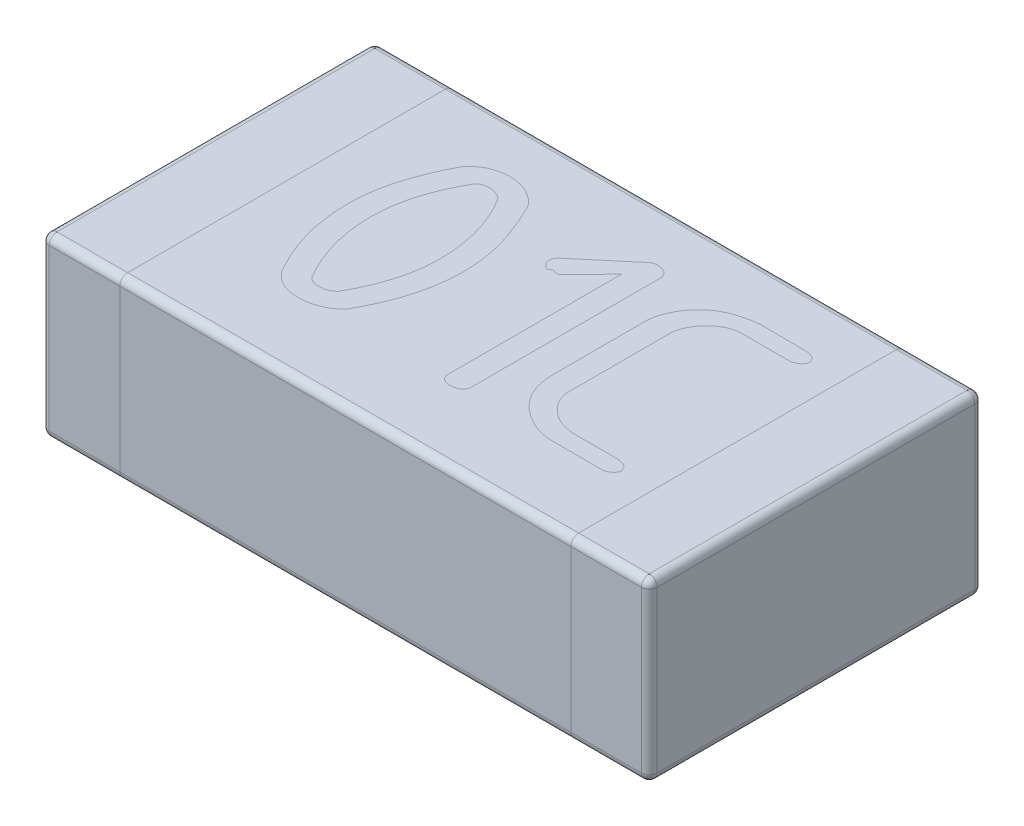
SolidWorks part; units mm, degrees
ref_plane "Front Plane" through (0, 0, 0) normal (0, 0, 1) x (1, 0, 0)
ref_plane "Top Plane" through (0, 0, 0) normal (0, 1, 0) x (1, 0, 0)
ref_plane "Right Plane" through (0, 0, 0) normal (1, 0, 0) x (0, 0, -1)
sketch "Sketch1" plane through (0, 0, 0) normal (0, 1, 0) x (1, 0, 0)
  line L1 (-0.755, -0.425) -> (0.755, -0.425)
  line L2 (-0.775, -0.405) -> (-0.775, 0.405)
  line L3 (-0.755, 0.425) -> (0.755, 0.425)
  line L4 (0.775, -0.405) -> (0.775, 0.405)
  line L5 (-0.775, -0.425) -> (0.775, 0.425) construction
  line L6 (-0.775, 0.425) -> (0.775, -0.425) construction
  arc A4 (-0.775, -0.405) -> (-0.755, -0.425) centre (-0.755, -0.405) ccw
  arc A5 (0.755, -0.425) -> (0.775, -0.405) centre (0.755, -0.405) ccw
  arc A6 (0.775, 0.405) -> (0.755, 0.425) centre (0.755, 0.405) ccw
  arc A7 (-0.755, 0.425) -> (-0.775, 0.405) centre (-0.755, 0.405) ccw
  point P0 (0, 0)
  dimension "D4" = 0.02
  dimension "D1" = 1.55
  dimension "D2" = 0.85
extrude "Boss-Extrude1" add sketch "Sketch1" along normal mid plane 0.45
sketch "Sketch3" plane through (0, 0.225, 0) normal (0, 1, 0) x (1, 0, 0)
  line L0 (-0.575, 0) -> (0.575, 0) construction
  line L1 (-0.575, -0.5133) -> (-0.575, 0.5133)
  line L2 (0.575, -0.5133) -> (0.575, 0.5133)
  line L3 (0, -0.25) -> (0, 0.25) construction
  line L6 (-0.575, -0.25) -> (0.575, -0.25) construction
  text T0 "<b>01C</b>" font "SWIsop1" height 0.53
  point P4 (0, 0)
  point P8 (-0.575, 0)
  point P11 (0.575, 0)
  point P14 (0, 0)
  point P17 (0, -0.25)
  dimension "D1" = 1.15
  dimension "D2" = 0.5
sketch "Sketch4" plane through (0, 0, 0.425) normal (0, 0, 1) x (1, 0, 0)
  line L0 (-0.575, 0.225) -> (-0.575, -0.5946)
  line L1 (0.575, 0.225) -> (0.575, -0.5946)
sketch "Sketch5" plane through (0, 0, -0.425) normal (0, 0, -1) x (-1, 0, 0)
  line L0 (-0.575, 0.225) -> (-0.575, -0.5946) construction
  line L1 (-0.575, 0.225) -> (-0.575, -0.5946)
  line L2 (0.575, 0.225) -> (0.575, -0.5946) construction
  line L3 (0.575, 0.225) -> (0.575, -0.5946)
sketch "Sketch6" plane through (0, -0.225, 0) normal (0, -1, 0) x (1, 0, 0)
  line L0 (0.575, 0.5133) -> (0.575, -0.5133) construction
  line L1 (-0.575, 0.5133) -> (-0.575, -0.5133) construction
  line L2 (0.575, 0.5133) -> (0.575, -0.5133)
  line L3 (-0.575, 0.5133) -> (-0.575, -0.5133)
split line "Split Line2"
split line "Split Line3"
split line "Split Line4"
split line "Split Line5"
fillet "Fillet2" radius 0.02 24 edges at (0.665, -0.225, 0.425) (-0.665, -0.225, 0.425) (0, -0.225, 0.425) (-0.7691, -0.225, 0.4191) (-0.775, -0.225, 0) (-0.7691, -0.225, -0.4191) (0, -0.225, -0.425) (-0.665, -0.225, -0.425) (0.665, -0.225, -0.425) (0.7691, -0.225, -0.4191) (0.775, -0.225, 0) (0.7691, -0.225, 0.4191) (-0.7691, 0.225, 0.4191) (-0.775, 0.225, 0) (-0.7691, 0.225, -0.4191) (0, 0.225, -0.425) (-0.665, 0.225, -0.425) (0.665, 0.225, -0.425) (0.7691, 0.225, -0.4191) (0.775, 0.225, 0) (0.7691, 0.225, 0.4191) (0.665, 0.225, 0.425) (-0.665, 0.225, 0.425) (0, 0.225, 0.425)
